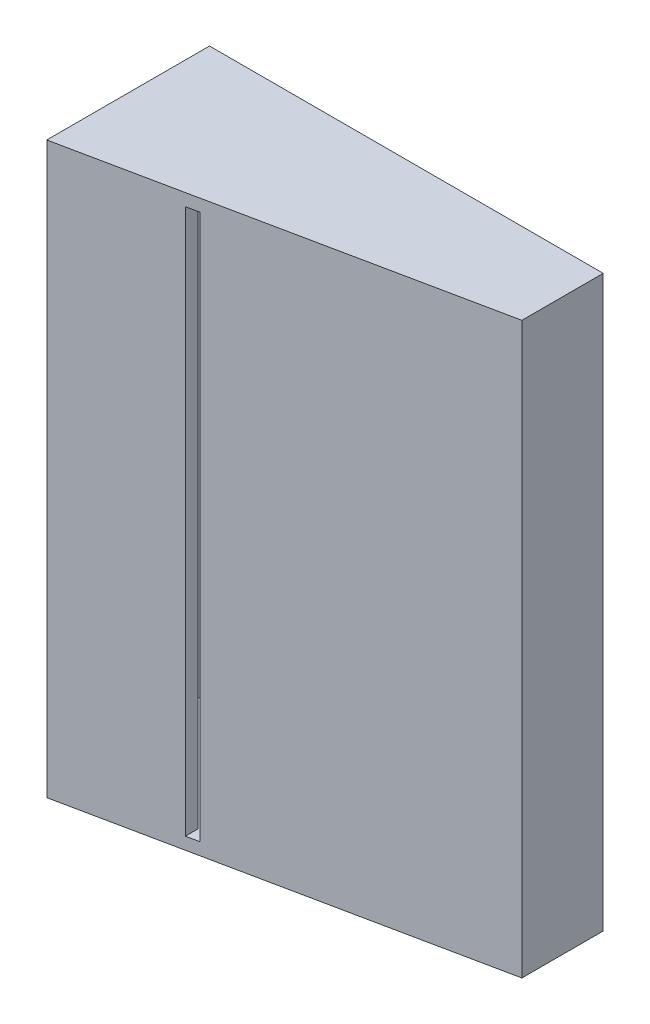
SolidWorks part; units mm, degrees
ref_plane "Front Plane" through (0, 0, 0) normal (0, 0, 1) x (1, 0, 0)
ref_plane "Top Plane" through (0, 0, 0) normal (0, 1, 0) x (1, 0, 0)
ref_plane "Right Plane" through (0, 0, 0) normal (1, 0, 0) x (0, 0, -1)
sketch "Sketch1" plane through (0, 0, 0) normal (0, 0, 1) x (1, 0, 0)
  line L3 (-46.8875, 15.35) -> (-46.8875, 35.15)
  line L6 (-46.8875, 35.15) -> (-43.9875, 35.15)
  line L7 (-43.9875, 15.35) -> (-46.8875, 15.35)
  line L8 (-43.9875, 35.15) -> (-43.9875, 15.35)
  line L9 (-46.8875, 35.15) -> (-43.9875, 35.15)
  line L10 (-43.9875, 15.35) -> (-46.8875, 15.35)
  line L11 (-43.9875, 35.15) -> (-43.9875, 15.35)
  dimension "D1" = 0.1
extrude "Boss-Extrude1" add sketch "Sketch1" against normal up to surface (1.5 mm away)
sketch "Sketch2" plane through (0, 0, -1.5) normal (0, 0, -1) x (-1, 0, 0)
  line L0 (46.8875, 15.35) -> (46.8875, 35.15) construction
  line L1 (24.3875, 12.25) -> (46.8875, 12.25)
  line L2 (24.3875, 12.25) -> (24.3875, 38.25)
  line L3 (24.3875, 38.25) -> (46.8875, 38.25)
  line L4 (46.8875, 12.25) -> (46.8875, 38.25)
  line L5 (24.3875, 12.25) -> (46.8875, 38.25) construction
  line L6 (24.3875, 38.25) -> (46.8875, 12.25) construction
  line L7 (43.8875, 35.25) -> (43.8875, 15.25) construction
  line L8 (46.8875, 35.25) -> (43.8875, 35.25) construction
  line L9 (24.3875, 26.75) -> (24.3875, 23.75) construction
  point P0 (35.6375, 25.25)
  point P10 (43.8875, 25.25)
  dimension "D1" = 3
extrude "Boss-Extrude3" add sketch "Sketch2" along normal blind 1.5
sketch "Sketch3" plane through (0, 0, 0) normal (0, 0, 1) x (1, 0, 0)
  line L0 (-46.8875, 15.25) -> (-46.8875, 35.25)
  line L8 (-43.8875, 35.25) -> (-43.8875, 15.25)
  line L9 (-43.8875, 15.25) -> (-46.8875, 15.25)
  line L10 (-46.8875, 15.25) -> (-46.8875, -9.75)
  line L11 (-46.8875, -9.75) -> (1.5, -9.75)
  line L12 (1.5, -9.75) -> (1.5, 60.25)
  line L13 (1.5, 60.25) -> (-46.8875, 60.25)
  line L14 (-46.8875, 60.25) -> (-46.8875, 35.25)
  line L15 (-46.8875, 35.25) -> (-43.8875, 35.25)
  line L18 (-46.8875, 15.25) -> (-46.8875, -9.75)
  line L19 (-46.8875, -9.75) -> (1.5, -9.75)
  line L20 (1.5, -9.75) -> (1.5, 60.25)
  line L21 (1.5, 60.25) -> (-46.8875, 60.25)
  line L22 (-46.8875, 60.25) -> (-46.8875, 35.25)
  dimension "D1" = 0
extrude "Boss-Extrude4" add sketch "Sketch3" along normal blind 20
sketch "Sketch4" plane through (0, -9.75, 0) normal (0, -1, 0) x (1, 0, 0)
  line L0 (-46.8875, 20) -> (1.5, 10)
  line L1 (1.5, 10) -> (1.5, 20)
  line L2 (1.5, 20) -> (-46.8875, 20)
  line L3 (1.5, 20) -> (1.5, 0) construction
  dimension "D1" = 10
extrude "Cut-Extrude1" cut sketch "Sketch4" against normal up to surface (70 mm away) up to face at (-22.6937, 60.25, 10)
ref_plane "Plane1" through (0, 25.25, 0) normal (0, 1, 0) x (1, 0, 0)
sketch "Sketch5" plane through (0, -9.75, 0) normal (0, -1, 0) x (1, 0, 0)
  line L4 (-46.8875, 20) -> (-46.8875, 0) construction
  line L8 (0, 1.5) -> (0, 8.7783)
  line L9 (0, 8.7783) -> (-45.3875, 18.1583)
  line L10 (-45.3875, 18.1583) -> (-45.3875, 1.5)
  line L11 (-45.3875, 1.5) -> (0, 1.5)
  line L12 (0, 1.5) -> (0, 8.7783)
  line L13 (0, 8.7783) -> (-46.8875, 18.4683)
  line L14 (-46.8875, 18.4683) -> (-46.8875, 1.5)
  line L15 (-46.8875, 1.5) -> (0, 1.5)
  dimension "D1" = 1.5
extrude "Cut-Extrude2" cut sketch "Sketch5" along normal up to surface (33.5 mm away) from offset 1.5
mirror "Mirror1" about plane through (0, 25.25, 0) normal (0, 1, 0) of "Cut-Extrude2"
sketch "Sketch6" plane through (0, 0, 0) normal (0, 0, -1) x (-1, 0, 0)
  line L0 (11, 25.25) -> (-11, 25.25) construction
  line L1 (32.77, 58.75) -> (31.27, 58.75)
  line L2 (32.77, 58.75) -> (32.77, -8.25)
  line L3 (32.77, -8.25) -> (31.27, -8.25)
  line L4 (31.27, 58.75) -> (31.27, -8.25)
  line L5 (32.77, 58.75) -> (31.27, -8.25) construction
  line L6 (32.77, -8.25) -> (31.27, 58.75) construction
  line L8 (46.8875, 58.75) -> (0, 58.75) construction
  line L9 (0, 58.75) -> (0, -8.25) construction
  point P0 (32.02, 25.25)
  dimension "D1" = 1.5
  dimension "D2" = 31.27
extrude "Cut-Extrude3" cut sketch "Sketch6" against normal up to surface (17.0824 mm away)
